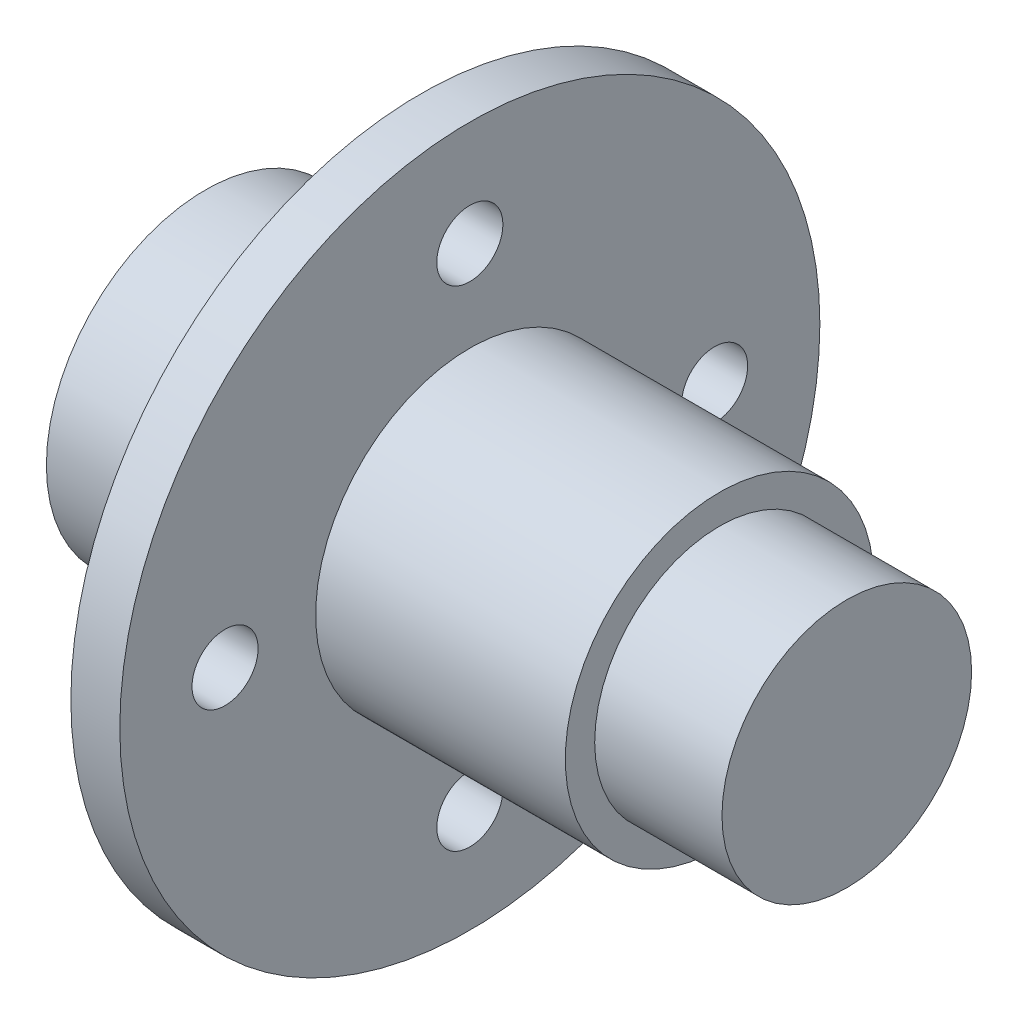
SolidWorks part; units mm, degrees
ref_plane "Alzado" through (0, 0, 0) normal (0, 0, 1) x (1, 0, 0)
ref_plane "Planta" through (0, 0, 0) normal (0, 1, 0) x (1, 0, 0)
ref_plane "Vista lateral" through (0, 0, 0) normal (1, 0, 0) x (0, 0, -1)
sketch "Sketch1" plane through (0, 0, 0) normal (0, 0, 1) x (1, 0, 0)
  line L0 (-32.4772, 0) -> (-32.4772, 32.5)
  line L1 (55, 0) -> (-55, 0) construction
  line L2 (-32.4772, 32.5) -> (11.5228, 32.5)
  line L3 (11.5228, 32.5) -> (11.5228, 71.5)
  line L4 (11.5228, 71.5) -> (21.5228, 71.5)
  line L5 (21.5228, 71.5) -> (21.5228, 31.5)
  line L6 (21.5228, 31.5) -> (72.5228, 31.5)
  line L7 (72.5228, 31.5) -> (72.5228, 25.5)
  line L8 (72.5228, 25.5) -> (98.5228, 25.5)
  line L9 (98.5228, 25.5) -> (98.5228, 0)
  line L10 (98.5228, 0) -> (-32.4772, 0)
  dimension "D1" = 32.5
  dimension "D2" = 10
  dimension "D3" = 51
  dimension "D4" = 105
  dimension "D5" = 26
  dimension "D6" = 25.5
  dimension "D7" = 31.5
  dimension "D8" = 71.5
revolve "Revolve1" add sketch "Sketch1" angle 360 about L10
hole_wizard "M12 Clearance Hole1" positions "3DSketch1" profile "Sketch2" hole size "M12" standard "ISO" end condition through all
sketch3d "3DSketch1"
  point P0 (21.5228, 50, 0)
  dimension "D1" = 0
  dimension "D2" = 50
sketch "Sketch2" plane through (21.5228, 50, 0) normal (0, 1, 0) x (0, 0, -1)
  line L0 (0, 0) -> (0, 54)
  line L1 (0, 54) -> (6.75, 54)
  line L2 (6.75, 54) -> (6.75, 0)
  line L5 (6.75, 0) -> (0, 0)
  line L11 (0, -6.35) -> (0, 107.95) construction
  dimension "Thru Hole Dia." = 13.5
  dimension "Thru Hole Depth" = 54
pattern_circular "CirPattern1" count 4 every 90 about axis through (0, 0, 0) along (1, 0, 0) of "M12 Clearance Hole1"
